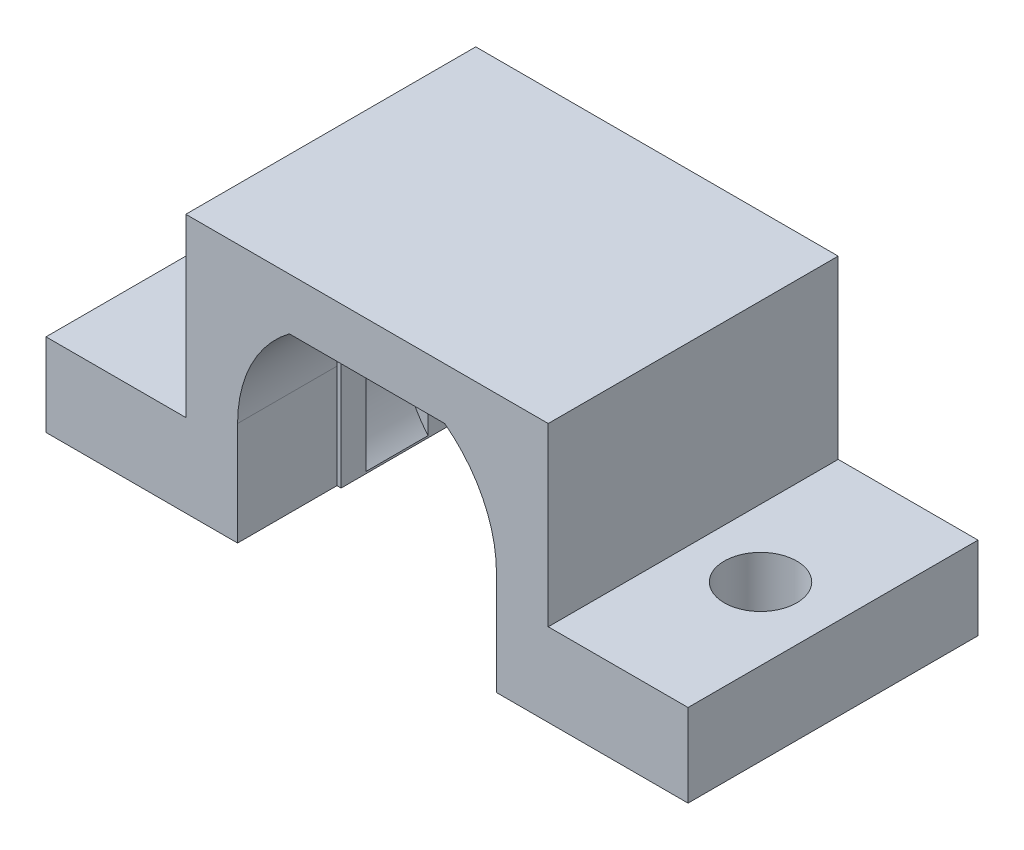
SolidWorks part; units mm, degrees
ref_plane "Plan de face" through (0, 0, 0) normal (0, 0, 1) x (1, 0, 0)
ref_plane "Plan de dessus" through (0, 0, 0) normal (0, 1, 0) x (1, 0, 0)
ref_plane "Plan de droite" through (0, 0, 0) normal (1, 0, 0) x (0, 0, -1)
sketch "Esquisse1" plane through (0, 0, 0) normal (0, 0, 1) x (1, 0, 0)
  line L0 (-15.5, 0) -> (-6.25, 0)
  line L1 (15.5, 0) -> (15.5, 4)
  line L2 (15.5, 4) -> (8.75, 4)
  line L3 (8.75, 4) -> (8.75, 12.5)
  line L4 (8.75, 12.5) -> (-8.75, 12.5)
  line L5 (-8.75, 12.5) -> (-8.75, 4)
  line L6 (-8.75, 4) -> (-15.5, 4)
  line L7 (-15.5, 4) -> (-15.5, 0)
  line L8 (-6.25, 5) -> (-6.25, 0)
  line L9 (-3.75, 10) -> (3.75, 10)
  line L10 (6.25, 0) -> (15.5, 0)
  line L11 (6.25, 5) -> (6.25, 0)
  line L12 (0, 10) -> (0, 0) construction
  arc A0 (-3.75, 10) -> (-6.25, 5) centre (0, 5) ccw
  arc A1 (6.25, 5) -> (3.75, 10) centre (0, 5) ccw
  dimension "D1" = 10
  dimension "D2" = 12.5
  dimension "D3" = 31
  dimension "D4" = 4
  dimension "D5" = 2.5
  dimension "D6" = 2.5
extrude "Boss.-Extru.1" add sketch "Esquisse1" along normal mid plane 14
sketch "Esquisse2" plane through (0, 4, 0) normal (0, 1, 0) x (1, 0, 0)
  line L0 (-12, 0) -> (12, 0) construction
  line L1 (-8.75, -7) -> (8.75, -7) construction
  line L4 (-9.1, -1.6743) -> (-9.1, 1.6743)
  line L5 (-9.1, 1.6743) -> (-12, 3.3486)
  line L6 (-12, 3.3486) -> (-14.9, 1.6743)
  line L7 (-14.9, 1.6743) -> (-14.9, -1.6743)
  line L8 (-14.9, -1.6743) -> (-12, -3.3486)
  line L9 (-12, -3.3486) -> (-9.1, -1.6743)
  line L10 (9.1, -1.6743) -> (12, -3.3486)
  line L11 (12, -3.3486) -> (14.9, -1.6743)
  line L12 (14.9, -1.6743) -> (14.9, 1.6743)
  line L13 (14.9, 1.6743) -> (12, 3.3486)
  line L14 (12, 3.3486) -> (9.1, 1.6743)
  line L15 (9.1, 1.6743) -> (9.1, -1.6743)
  circle A0 centre (-12, 0) radius 2.9 construction
  circle A1 centre (12, 0) radius 2.9 construction
  dimension "D1" = 5.8
  dimension "D2" = 24
extrude "Enlèv. mat.-Extru.1" cut sketch "Esquisse2" against normal blind 1.5
sketch "Esquisse3" plane through (0, 2.5, 0) normal (0, 1, 0) x (1, 0, 0)
  circle A0 centre (-12, 0) radius 1.75
  circle A1 centre (12, 0) radius 1.75
  dimension "D1" = 3.5
extrude "Enlèv. mat.-Extru.2" cut sketch "Esquisse3" against normal blind 8.5
sketch "Esquisse4" plane through (0, 0, -7) normal (0, 0, -1) x (-1, 0, 0)
  line L0 (6.25, 0) -> (6.25, 5) construction
  line L1 (6.25, 5) -> (-6.25, 5)
  line L2 (6.25, 5) -> (6.25, 10)
  line L3 (6.25, 10) -> (-6.25, 10)
  line L4 (-6.25, 5) -> (-6.25, 10)
  line L5 (-6.25, 5) -> (-6.25, 0) construction
  line L6 (3.75, 10) -> (-3.75, 10) construction
extrude "Enlèv. mat.-Extru.3" cut sketch "Esquisse4" against normal blind 9.2
sketch "Esquisse5" plane through (0, 0, 2.2) normal (0, 0, -1) x (-1, 0, 0)
  line L0 (-3.75, 10) -> (-6.25, 5)
  line L2 (-3.75, 10) -> (-6.25, 10)
  line L3 (-6.25, 10) -> (-6.25, 5)
  line L4 (-3.75, 10) -> (-6.25, 10)
  line L5 (-6.25, 10) -> (-6.25, 5)
  arc A1 (-3.75, 10) -> (-6.25, 5) centre (0, 5) ccw
  dimension "D1" = 0
extrude "Boss.-Extru.2" add sketch "Esquisse5" along normal blind 1.8 from offset 1.2
sketch "Esquisse8" plane through (0, 0, 0) normal (0, -1, 0) x (1, 0, 0)
  line L0 (3.75, 2.2) -> (6.25, 2.2) construction
  line L1 (6.05, 2.2) -> (6.25, 2.2)
  line L2 (6.05, 2.2) -> (6.05, -7)
  line L3 (6.05, -7) -> (6.25, -7)
  line L4 (6.25, 2.2) -> (6.25, -7)
  line L5 (-6.25, 2.2) -> (-3.75, 2.2) construction
  line L6 (-6.05, 2.2) -> (-6.25, 2.2)
  line L7 (-6.05, 2.2) -> (-6.05, -7)
  line L8 (-6.05, -7) -> (-6.25, -7)
  line L9 (-6.25, 2.2) -> (-6.25, -7)
  dimension "D1" = 12.1
extrude "Boss.-Extru.3" add sketch "Esquisse8" against normal up to surface (10 mm away) up to face at (1.6667, 10, 0.7667)
sketch "Esquisse6" plane through (0, 0, 1) normal (0, 0, 1) x (1, 0, 0)
  circle A0 centre (-2.7867, 3.0155) radius 4.3797
extrude "Enlèv. mat.-Extru.4" cut sketch "Esquisse6" against normal blind 3
sketch "Esquisse7" plane through (0, 0, -0.8) normal (0, 0, -1) x (-1, 0, 0)
  circle A0 centre (-3.1184, 6.4988) radius 4.1664
extrude "Enlèv. mat.-Extru.5" cut sketch "Esquisse7" along normal blind 2 from offset 1
sketch "Esquisse9" plane through (0, 2.5, 0) normal (0, 1, 0) x (1, 0, 0)
  line L6 (9.1, 1.6743) -> (9.1, -1.6743)
  line L7 (9.1, -1.6743) -> (12, -3.3486)
  line L8 (12, -3.3486) -> (14.9, -1.6743)
  line L9 (14.9, -1.6743) -> (14.9, 1.6743)
  line L10 (14.9, 1.6743) -> (12, 3.3486)
  line L11 (12, 3.3486) -> (9.1, 1.6743)
  line L12 (9.1, 1.6743) -> (9.1, -1.6743)
  line L13 (9.1, -1.6743) -> (12, -3.3486)
  line L14 (12, -3.3486) -> (14.9, -1.6743)
  line L15 (14.9, -1.6743) -> (14.9, 1.6743)
  line L16 (14.9, 1.6743) -> (12, 3.3486)
  line L17 (12, 3.3486) -> (9.1, 1.6743)
  line L18 (-12, -3.3486) -> (-9.1, -1.6743)
  line L19 (-9.1, -1.6743) -> (-9.1, 1.6743)
  line L20 (-9.1, 1.6743) -> (-12, 3.3486)
  line L21 (-12, 3.3486) -> (-14.9, 1.6743)
  line L22 (-14.9, 1.6743) -> (-14.9, -1.6743)
  line L23 (-14.9, -1.6743) -> (-12, -3.3486)
  line L24 (-12, -3.3486) -> (-9.1, -1.6743)
  line L25 (-9.1, -1.6743) -> (-9.1, 1.6743)
  line L26 (-9.1, 1.6743) -> (-12, 3.3486)
  line L27 (-12, 3.3486) -> (-14.9, 1.6743)
  line L28 (-14.9, 1.6743) -> (-14.9, -1.6743)
  line L29 (-14.9, -1.6743) -> (-12, -3.3486)
  circle A0 centre (12, 0) radius 1.75 construction
  circle A1 centre (-12, 0) radius 1.75 construction
  circle A2 centre (12, 0) radius 1.75
  circle A3 centre (-12, 0) radius 1.75
  dimension "D1" = 0
  dimension "D2" = 0
extrude "Boss.-Extru.4" add sketch "Esquisse9" along normal blind 1.5
